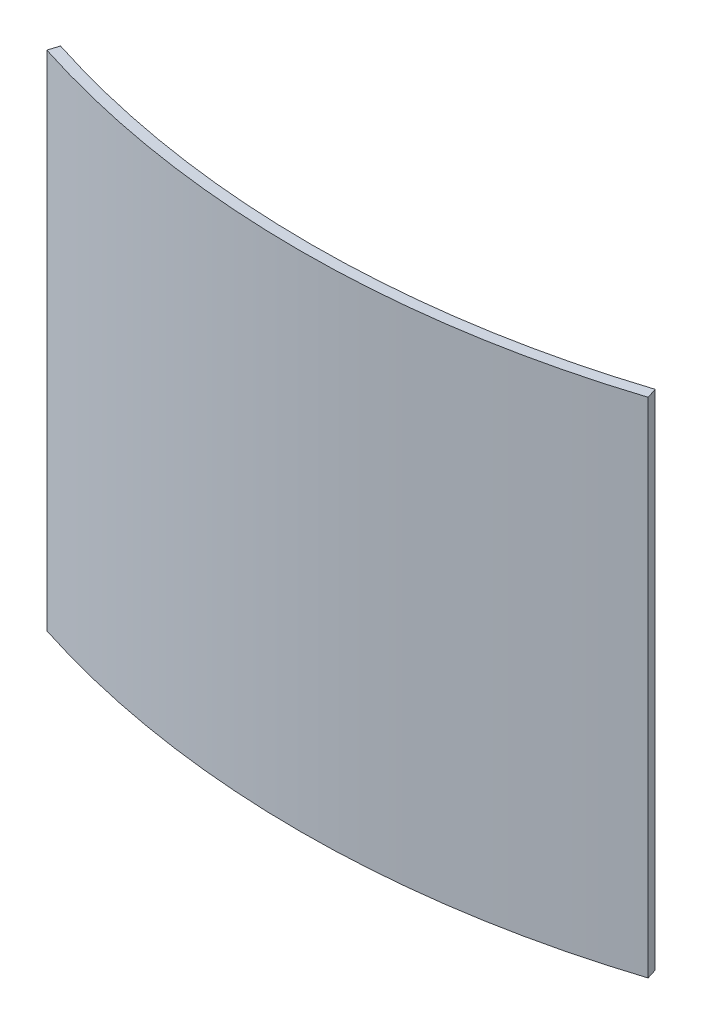
SolidWorks part; units mm, degrees
ref_plane "Plano frontal" through (0, 0, 0) normal (0, 0, 1) x (1, 0, 0)
ref_plane "Plano superior" through (0, 0, 0) normal (0, 1, 0) x (1, 0, 0)
ref_plane "Plano direito" through (0, 0, 0) normal (1, 0, 0) x (0, 0, -1)
sketch "Esboço1" plane through (0, 0, 0) normal (0, 1, 0) x (1, 0, 0)
  line L0 (0, 0) -> (0, -40) construction
  line L1 (0, 0) -> (-275, 0) construction
  line L2 (0, 0) -> (275, 0) construction
  arc A0 (275, 0) -> (-275, 0) centre (0, 856.9568) cw
  dimension "D1" = 275
  dimension "D3" = 40
  dimension "D4" = 900
  dimension "D2" = 275
extrude "Extrusão-Fina1" add sketch "Esboço1" along normal blind 230 and the other way blind 230 thin
